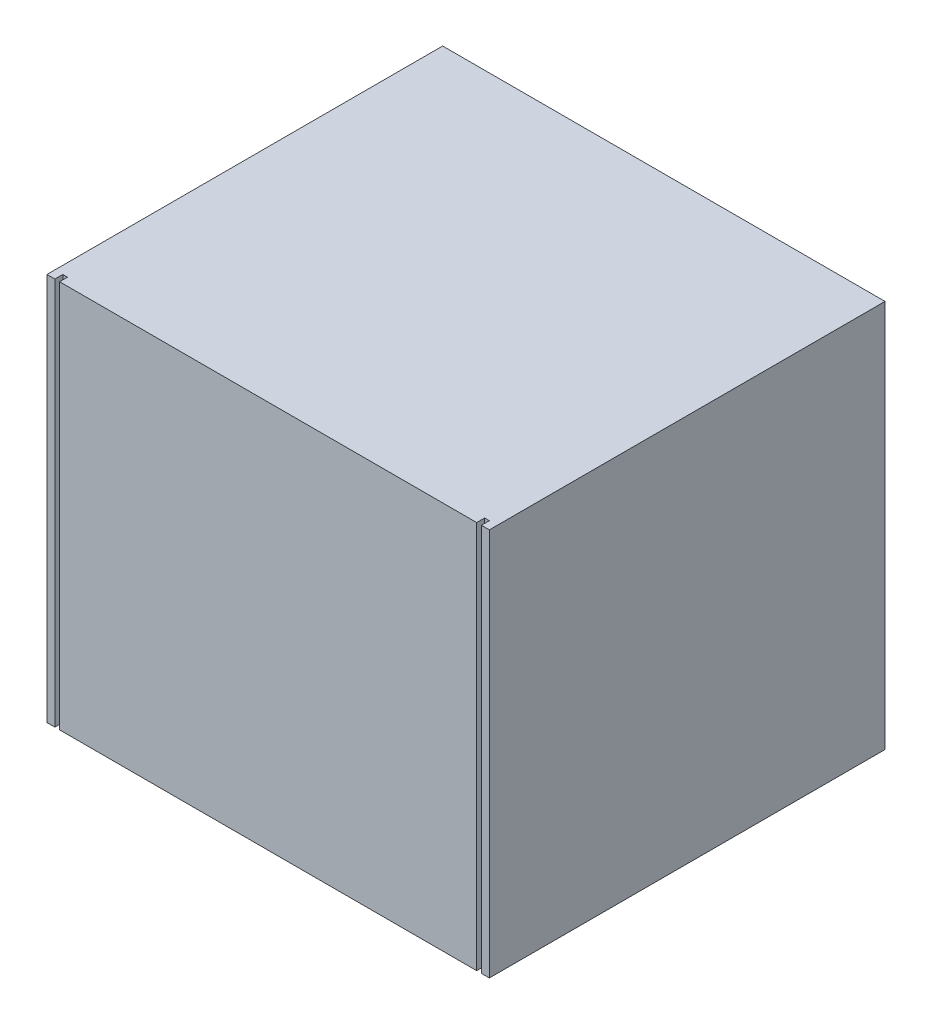
SolidWorks part; units mm, degrees
other "标注1"
sketch "草图8" plane through (561.7433, -144.5476, -100) normal (0.561, 0.6285, -0.5388) x (0.8242, -0.4852, 0.2922)
ref_plane "前视基准面" through (0, 0, 0) normal (0, 0, 1) x (1, 0, 0)
ref_plane "上视基准面" through (0, 0, 0) normal (0, 1, 0) x (1, 0, 0)
ref_plane "右视基准面" through (0, 0, 0) normal (1, 0, 0) x (0, 0, -1)
sketch "草图2" plane through (180.8379, -79.0358, 0) normal (0, 0, 1) x (1, 0, 0)
  line L0 (-178.11, 123.9732) -> (-178.11, -556.0268)
  line L1 (-178.11, -556.0268) -> (380.9054, -556.0268)
  line L2 (380.9054, -556.0268) -> (380.9054, 123.9732)
  line L3 (380.9054, 123.9732) -> (-178.11, 123.9732)
  dimension "D1" = 559.0153
  dimension "D2" = 680
extrude "凸台-拉伸2" add sketch "草图2" along normal blind 400
sketch "草图3" plane through (180.8379, -79.0358, 400) normal (0, 0, 1) x (1, 0, 0)
  line L0 (-178.11, -65.5118) -> (380.9054, -65.5118)
  line L1 (380.9054, -556.0268) -> (380.9054, 123.9732) construction
  line L3 (-178.11, -556.0268) -> (380.9054, -556.0268) construction
  line L13 (-178.11, 123.9732) -> (-178.11, -556.0268) construction
  line L14 (380.9054, -65.5118) -> (380.9054, -555.9447)
  line L15 (380.9054, -275.4234) -> (380.9054, -1075.4234) construction
  line L16 (380.9054, -555.9447) -> (-178.11, -555.9447)
  line L17 (-178.11, -555.9447) -> (-178.11, -65.5118)
  arc A0 (568.6892, -162.2209) -> (-323.5511, -162.2209) centre (122.569, -675.4234) ccw construction
  arc A1 (568.6892, -162.2209) -> (-323.5511, -162.2209) centre (122.569, -675.4234) ccw construction
extrude "切除-拉伸1" cut sketch "草图3" against normal through all flip side to cut
sketch "草图4" plane through (180.8379, -79.0358, 0) normal (0, 0, -1) x (-1, 0, 0)
  line L4 (178.11, -65.5118) -> (-380.9054, -65.5118)
  line L5 (-380.9054, -65.5118) -> (-380.9054, -555.9447)
  line L6 (-380.9054, -555.9447) -> (178.11, -555.9447)
  line L7 (178.11, -555.9447) -> (178.11, -65.5118)
  line L8 (178.11, -65.5118) -> (-380.9054, -65.5118)
  line L10 (-380.9054, -555.9447) -> (178.11, -555.9447)
  line L11 (178.11, -555.9447) -> (178.11, -65.5118)
  line L13 (-380.9054, -65.5118) -> (-380.9054, -555.9447)
  dimension "D1" = 0
extrude "凸台-拉伸3" add sketch "草图4" along normal blind 100
shell "抽壳2" thickness 30
sketch "草图5" plane through (0, -174.5476, 0) normal (0, -1, 0) x (1, 0, 0)
  line L0 (531.7433, -100) -> (531.7433, -90) construction
  line L1 (531.7433, -100) -> (531.7433, 370) construction
  line L2 (531.7433, -90) -> (32.728, -90) construction
  line L3 (32.728, -100) -> (32.728, 370) construction
  line L4 (32.728, -90) -> (32.728, -100) construction
  line L5 (32.728, -100) -> (531.7433, -100) construction
  line L6 (531.7433, -90) -> (531.7433, -84)
  line L7 (531.7433, -84) -> (32.728, -84)
  line L8 (32.728, -84) -> (32.728, -90)
  line L9 (531.7433, -90) -> (32.728, -90)
  dimension "D1" = 10
  dimension "D2" = 6
extrude "切除-拉伸2" cut sketch "草图5" against normal blind 10
sketch "草图6" plane through (0, -174.5476, 0) normal (0, -1, 0) x (1, 0, 0)
  line L0 (531.7433, -84) -> (531.7433, -79) construction
  line L1 (531.7433, -84) -> (531.7433, 370) construction
  line L2 (531.7433, -79) -> (32.728, -79) construction
  line L3 (32.728, -84) -> (32.728, 370) construction
  line L4 (32.728, -79) -> (32.728, -84) construction
  line L5 (32.728, -84) -> (531.7433, -84) construction
  line L6 (531.7433, -79) -> (531.7433, -73)
  line L7 (531.7433, -73) -> (32.728, -73)
  line L8 (32.728, -73) -> (32.728, -79)
  line L9 (32.728, -79) -> (531.7433, -79)
  dimension "D1" = 5
  dimension "D2" = 6
extrude "切除-拉伸3" cut sketch "草图6" against normal blind 10
ref_plane "基准面1" through (0, -389.764, 0) normal (0, -1, 0) x (-1, 0, 0)
mirror "镜向1" about plane through (0, -389.764, 0) normal (0, -1, 0) of "切除-拉伸3", "切除-拉伸2"
sketch "草图7" plane through (0, 0, 400) normal (0, 0, 1) x (1, 0, 0)
  line L0 (561.7433, -144.5476) -> (551.7433, -144.5476) construction
  line L1 (561.7433, -144.5476) -> (2.728, -144.5476) construction
  line L2 (551.7433, -144.5476) -> (551.7433, -634.9805) construction
  line L3 (2.728, -634.9805) -> (561.7433, -634.9805) construction
  line L4 (551.7433, -634.9805) -> (561.7433, -634.9805) construction
  line L5 (561.7433, -634.9805) -> (561.7433, -144.5476) construction
  line L6 (551.7433, -144.5476) -> (545.7433, -144.5476)
  line L7 (545.7433, -144.5476) -> (545.7433, -634.9805)
  line L8 (545.7433, -634.9805) -> (551.7433, -634.9805)
  line L9 (551.7433, -634.9805) -> (551.7433, -144.5476)
  point P13 (551.7433, -144.4611)
  dimension "D1" = 10
  dimension "D2" = 6
extrude "切除-拉伸4" cut sketch "草图7" against normal blind 10
ref_plane "基准面2" through (282.2356, 0, 0) normal (-1, 0, 0) x (0, 0, 1)
mirror "镜向2" about plane through (282.2356, 0, 0) normal (-1, 0, 0) of "切除-拉伸4"
